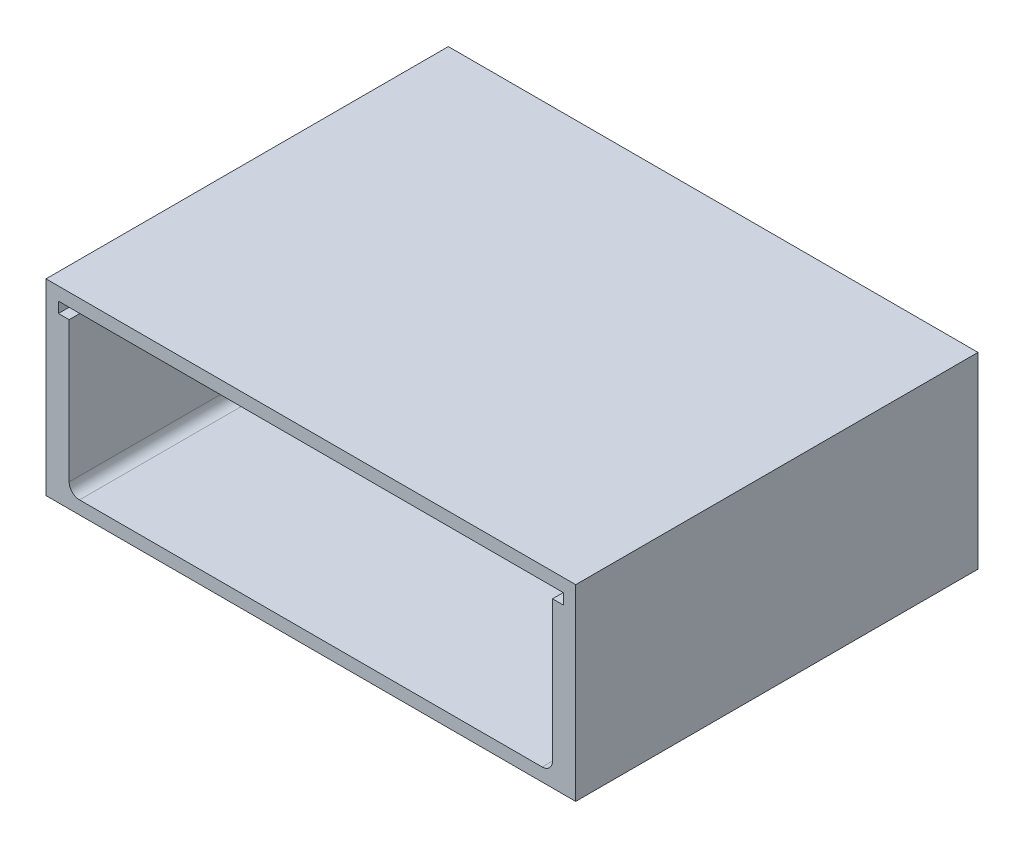
SolidWorks part; units mm, degrees
ref_plane "Front Plane" through (0, 0, 0) normal (0, 0, 1) x (1, 0, 0)
ref_plane "Top Plane" through (0, 0, 0) normal (0, 1, 0) x (1, 0, 0)
ref_plane "Right Plane" through (0, 0, 0) normal (1, 0, 0) x (0, 0, -1)
sketch "Sketch1" plane through (0, 0, 0) normal (0, 0, 1) x (1, 0, 0)
  line L1 (0, 0) -> (79, 0)
  line L2 (0, 0) -> (0, 28)
  line L3 (0, 28) -> (79, 28)
  line L4 (79, 0) -> (79, 28)
  dimension "D1" = 28
  dimension "D2" = 79
extrude "Boss-Extrude1" add sketch "Sketch1" along normal blind 60
sketch "Sketch2" plane through (0, 0, 60) normal (0, 0, 1) x (1, 0, 0)
  line L0 (0, 28) -> (0, 0) construction
  line L1 (3.45, 26.05) -> (75.6, 26.05)
  line L2 (3.45, 24.45) -> (3.45, 1.95)
  line L3 (3.45, 1.95) -> (75.55, 1.95)
  line L4 (75.55, 24.45) -> (75.55, 1.95)
  line L5 (79, 0) -> (79, 28) construction
  line L6 (0, 0) -> (79, 0) construction
  line L7 (79, 28) -> (0, 28) construction
  line L9 (3.45, 26.05) -> (1.85, 26.05)
  line L11 (3.45, 24.45) -> (1.85, 24.45)
  line L12 (1.85, 26.05) -> (1.85, 24.45)
  line L13 (75.6, 26.05) -> (77.15, 26.05)
  line L15 (75.55, 24.45) -> (77.15, 24.45)
  line L16 (77.15, 26.05) -> (77.15, 24.45)
  dimension "D1" = 3.45
  dimension "D2" = 3.45
  dimension "D3" = 1.95
  dimension "D4" = 1.95
  dimension "D5" = 1.6
  dimension "D6" = 1.6
  dimension "D7" = 1.6
  dimension "D8" = 1.6
  dimension "D9" = 24.1
  dimension "D10" = 72.1
extrude "Cut-Extrude1" cut sketch "Sketch2" against normal blind 46
sketch "Sketch3" plane through (0, 0, 14) normal (0, 0, 1) x (1, 0, 0)
  line L0 (75.55, 1.95) -> (75.55, 24.45) construction
  line L1 (74, 3.5) -> (48.26, 3.5)
  line L2 (74, 3.5) -> (74, 6.5)
  line L3 (74, 6.5) -> (48.26, 6.5)
  line L4 (48.26, 3.5) -> (48.26, 6.5)
  line L5 (3.45, 1.95) -> (75.55, 1.95) construction
  dimension "D1" = 3
  dimension "D2" = 25.74
  dimension "D3" = 1.55
  dimension "D4" = 1.55
extrude "Cut-Extrude2" cut sketch "Sketch3" against normal blind 26
sketch "Sketch4" plane through (0, 0, 14) normal (0, 0, 1) x (1, 0, 0)
  line L0 (6.45, 24.05) -> (72.55, 24.05)
  line L1 (72.55, 24.05) -> (72.55, 8.5)
  line L2 (72.55, 8.5) -> (46.26, 8.5)
  line L3 (46.26, 8.5) -> (46.26, 3.95)
  line L4 (46.26, 3.95) -> (6.45, 3.95)
  line L5 (6.45, 3.95) -> (6.45, 24.05)
  line L6 (3.45, 24.45) -> (3.45, 1.95) construction
  line L7 (77.15, 26.05) -> (1.85, 26.05) construction
  line L8 (3.45, 1.95) -> (75.55, 1.95) construction
  line L9 (48.26, 6.5) -> (48.26, 3.5) construction
  line L10 (74, 6.5) -> (48.26, 6.5) construction
  line L11 (75.55, 1.95) -> (75.55, 24.45) construction
  point P12 (48.26, 5)
  dimension "D1" = 3
  dimension "D2" = 2
  dimension "D3" = 2
  dimension "D4" = 2
  dimension "D5" = 2
  dimension "D6" = 3
extrude "Cut-Extrude3" cut sketch "Sketch4" against normal blind 26
fillet "Fillet1" radius 1.55 2 edges at (75.55, 1.95, 37) (3.45, 1.95, 37)
fillet "Fillet2" radius 2 6 edges at (72.55, 24.05, 7) (72.55, 8.5, 7) (46.26, 8.5, 7) (46.26, 3.95, 7) (6.45, 3.95, 7) (6.45, 24.05, 7)
